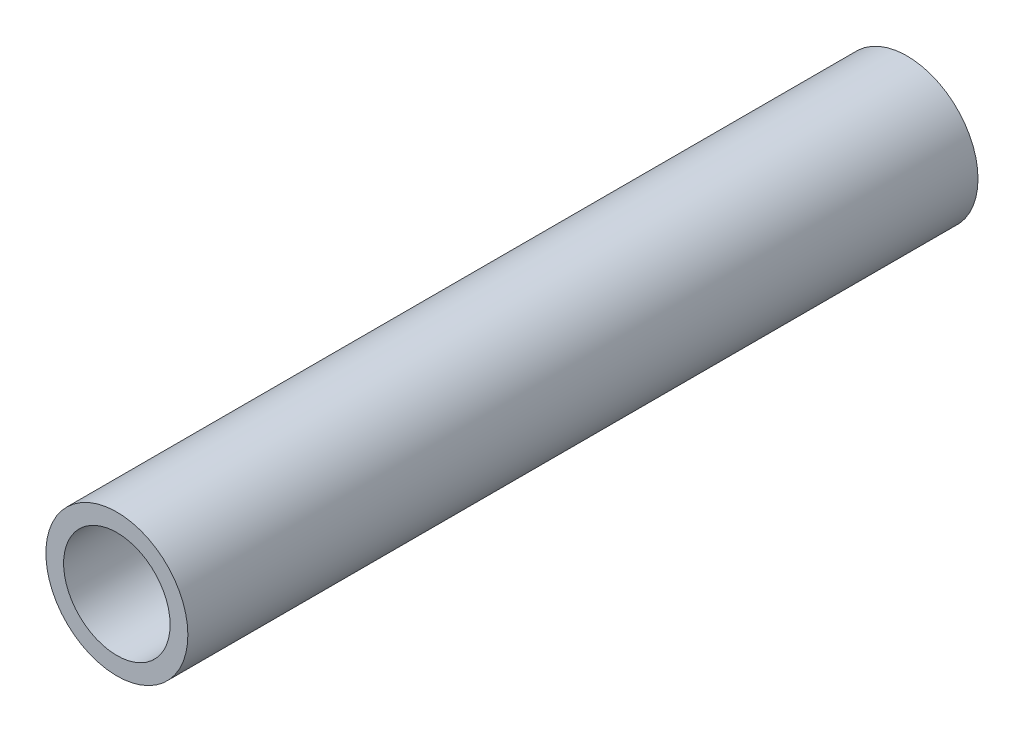
SolidWorks part; units mm, degrees
ref_plane "Front Plane" through (0, 0, 0) normal (0, 0, 1) x (1, 0, 0)
ref_plane "Top Plane" through (0, 0, 0) normal (0, 1, 0) x (1, 0, 0)
ref_plane "Right Plane" through (0, 0, 0) normal (1, 0, 0) x (0, 0, -1)
sketch "Sketch1" plane through (0, 0, 0) normal (0, 0, 1) x (1, 0, 0)
  circle A0 centre (0, 0) radius 20
  dimension "D1" = 40
extrude "Boss-Extrude1" add sketch "Sketch1" along normal blind 222.57
sketch "Sketch2" plane through (0, 0, 222.57) normal (0, 0, 1) x (1, 0, 0)
  circle A0 centre (0, 0) radius 15
  dimension "D1" = 30
extrude "Cut-Extrude1" cut sketch "Sketch2" against normal through all
